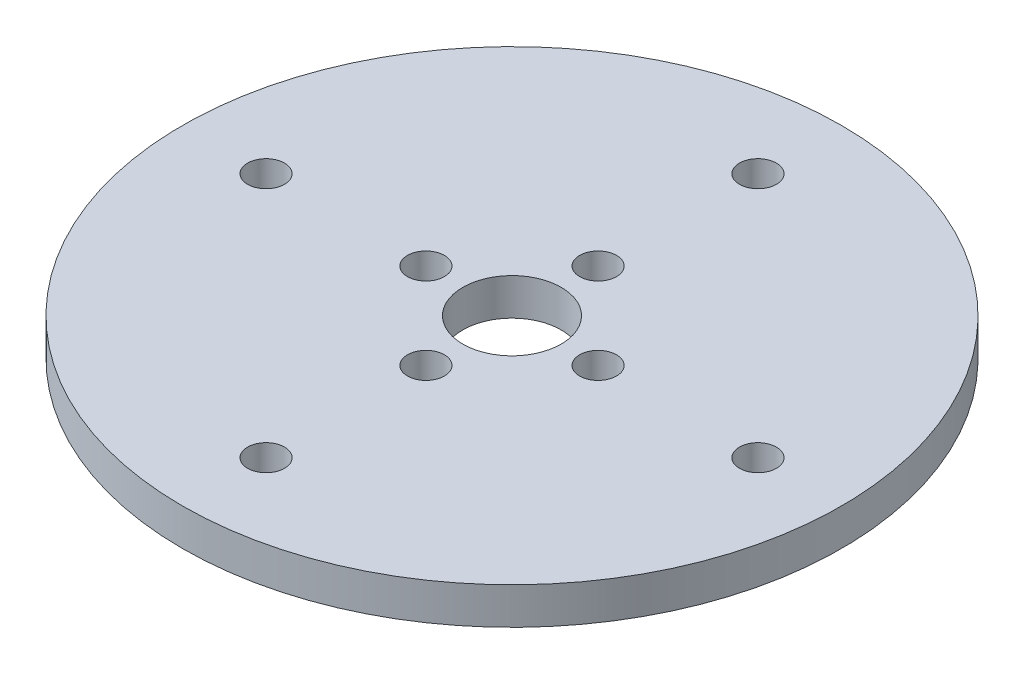
SolidWorks part; units mm, degrees
ref_plane "前视基准面" through (0, 0, 0) normal (0, 0, 1) x (1, 0, 0)
ref_plane "上视基准面" through (0, 0, 0) normal (0, 1, 0) x (1, 0, 0)
ref_plane "右视基准面" through (0, 0, 0) normal (1, 0, 0) x (0, 0, -1)
other "Configuration Table"
sketch "草图1" plane through (0, 0, 0) normal (0, 1, 0) x (1, 0, 0)
  circle A0 centre (0, 0) radius 26.8
  circle A3 centre (0, 0) radius 4
  circle A4 centre (0, 20) radius 1.5
  circle A5 centre (-20, 0) radius 1.5
  circle A6 centre (-7, 0) radius 1.5
  circle A7 centre (0, 7) radius 1.5
  circle A8 centre (0, -7) radius 1.5
  circle A9 centre (0, -20) radius 1.5
  circle A10 centre (7, 0) radius 1.5
  circle A11 centre (20, 0) radius 1.5
extrude "凸台-拉伸2" add sketch "草图1" along normal blind 3
